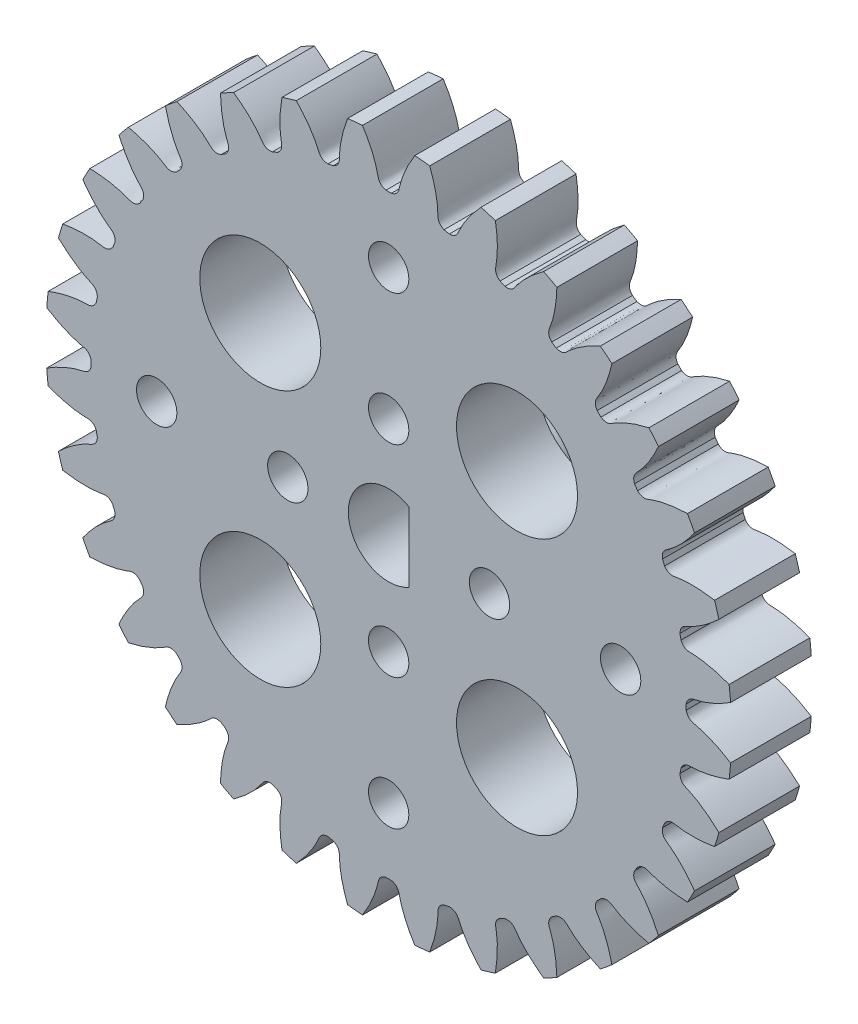
SolidWorks part; units mm, degrees
ref_plane "前视基准面" through (0, 0, 0) normal (0, 0, 1) x (1, 0, 0)
ref_plane "上视基准面" through (0, 0, 0) normal (0, 1, 0) x (1, 0, 0)
ref_plane "右视基准面" through (0, 0, 0) normal (1, 0, 0) x (0, 0, -1)
sketch "草图1" plane through (0, 0, 0) normal (0, 0, 1) x (1, 0, 0)
  arc A0 (-500.8621, -21.0203) -> (-500.9144, -20.7574) centre (-515.3543, -23.7663) ccw
  arc A1 (-500.9144, -26.7753) -> (-500.8621, -26.5123) centre (-515.3543, -23.7663) ccw
  arc A2 (-499.1979, -29.0552) -> (-498.9824, -28.3448) centre (-515.3543, -23.7663) ccw
  arc A3 (-501.7789, -29.5345) -> (-501.6763, -29.2869) centre (-515.3543, -23.7663) ccw
  arc A4 (-505.0196, -34.2905) -> (-504.8301, -34.101) centre (-515.3543, -23.7663) ccw
  arc A5 (-504.8591, -37.1399) -> (-504.2852, -36.6689) centre (-515.3543, -23.7663) ccw
  arc A6 (-507.2714, -36.1045) -> (-507.0485, -35.9555) centre (-515.3543, -23.7663) ccw
  arc A7 (-507.6698, -38.9304) -> (-507.0151, -38.5805) centre (-515.3543, -23.7663) ccw
  arc A8 (-509.8337, -37.4443) -> (-509.5861, -37.3417) centre (-515.3543, -23.7663) ccw
  arc A9 (-510.7758, -40.1382) -> (-510.0654, -39.9227) centre (-515.3543, -23.7663) ccw
  arc A10 (-512.6083, -38.2585) -> (-512.3453, -38.2062) centre (-515.3543, -23.7663) ccw
  arc A11 (-521.1224, -37.3417) -> (-520.8748, -37.4443) centre (-515.3543, -23.7663) ccw
  arc A12 (-523.6934, -38.5805) -> (-523.0388, -38.9304) centre (-515.3543, -23.7663) ccw
  arc A13 (-523.66, -35.9555) -> (-523.4371, -36.1045) centre (-515.3543, -23.7663) ccw
  arc A14 (-526.4233, -36.6689) -> (-525.8495, -37.1399) centre (-515.3543, -23.7663) ccw
  arc A15 (-525.8784, -34.101) -> (-525.6889, -34.2905) centre (-515.3543, -23.7663) ccw
  arc A16 (-528.7278, -34.2615) -> (-528.2568, -34.8354) centre (-515.3543, -23.7663) ccw
  arc A17 (-527.6924, -31.8492) -> (-527.5435, -32.0721) centre (-515.3543, -23.7663) ccw
  arc A18 (-530.5183, -31.4508) -> (-530.1684, -32.1055) centre (-515.3543, -23.7663) ccw
  arc A19 (-529.0322, -29.2869) -> (-528.9296, -29.5345) centre (-515.3543, -23.7663) ccw
  arc A20 (-531.7261, -28.3448) -> (-531.5106, -29.0552) centre (-515.3543, -23.7663) ccw
  arc A21 (-529.8464, -26.5123) -> (-529.7941, -26.7753) centre (-515.3543, -23.7663) ccw
  arc A22 (-529.7941, -20.7574) -> (-529.8464, -21.0203) centre (-515.3543, -23.7663) ccw
  arc A23 (-531.5106, -18.4775) -> (-531.7261, -19.1879) centre (-515.3543, -23.7663) ccw
  arc A24 (-528.9296, -17.9982) -> (-529.0322, -18.2458) centre (-515.3543, -23.7663) ccw
  arc A25 (-530.1684, -15.4272) -> (-530.5183, -16.0819) centre (-515.3543, -23.7663) ccw
  arc A26 (-527.5435, -15.4606) -> (-527.6924, -15.6835) centre (-515.3543, -23.7663) ccw
  arc A27 (-528.2568, -12.6973) -> (-528.7278, -13.2711) centre (-515.3543, -23.7663) ccw
  arc A28 (-525.6889, -13.2422) -> (-525.8784, -13.4317) centre (-515.3543, -23.7663) ccw
  arc A29 (-525.8495, -10.3928) -> (-526.4233, -10.8638) centre (-515.3543, -23.7663) ccw
  arc A30 (-523.4371, -11.4282) -> (-523.66, -11.5771) centre (-515.3543, -23.7663) ccw
  arc A31 (-523.0388, -8.6023) -> (-523.6934, -8.9522) centre (-515.3543, -23.7663) ccw
  arc A32 (-520.8748, -10.0884) -> (-521.1224, -10.191) centre (-515.3543, -23.7663) ccw
  arc A33 (-519.9327, -7.3945) -> (-520.6431, -7.61) centre (-515.3543, -23.7663) ccw
  arc A34 (-518.1003, -9.2742) -> (-518.3632, -9.3265) centre (-515.3543, -23.7663) ccw
  arc A35 (-515.2202, -9.017) -> (-515.4883, -9.017) centre (-515.3543, -23.7663) ccw
  arc A36 (-509.5861, -10.191) -> (-509.8337, -10.0884) centre (-515.3543, -23.7663) ccw
  arc A37 (-507.0485, -11.5771) -> (-507.2714, -11.4282) centre (-515.3543, -23.7663) ccw
  arc A38 (-504.8301, -13.4317) -> (-505.0196, -13.2422) centre (-515.3543, -23.7663) ccw
  arc A39 (-501.9808, -13.2711) -> (-502.4517, -12.6973) centre (-515.3543, -23.7663) ccw
  arc A40 (-503.0161, -15.6835) -> (-503.1651, -15.4606) centre (-515.3543, -23.7663) ccw
  arc A41 (-500.1902, -16.0819) -> (-500.5401, -15.4272) centre (-515.3543, -23.7663) ccw
  arc A42 (-501.6763, -18.2458) -> (-501.7789, -17.9982) centre (-515.3543, -23.7663) ccw
  arc A43 (-498.9824, -19.1879) -> (-499.1979, -18.4775) centre (-515.3543, -23.7663) ccw
  circle A44 centre (-515.3543, -23.7663) radius 2
  circle A45 centre (-510.3543, -23.7663) radius 1
  circle A46 centre (-515.3543, -18.7663) radius 1
  circle A47 centre (-520.3543, -23.7663) radius 1
  circle A48 centre (-515.3543, -28.7663) radius 1
  arc A49 (-498.4765, -25.8016) -> (-498.4038, -25.0629) centre (-515.3543, -23.7663) ccw
  arc A50 (-518.3632, -38.2062) -> (-518.1003, -38.2585) centre (-515.3543, -23.7663) ccw
  arc A51 (-512.3453, -9.3265) -> (-512.6083, -9.2742) centre (-515.3543, -23.7663) ccw
  arc A52 (-515.4883, -38.5157) -> (-515.2202, -38.5157) centre (-515.3543, -23.7663) ccw
  arc A53 (-514.0578, -40.7168) -> (-513.319, -40.6441) centre (-515.3543, -23.7663) ccw
  arc A54 (-517.3895, -40.6441) -> (-516.6508, -40.7168) centre (-515.3543, -23.7663) ccw
  arc A55 (-520.6431, -39.9227) -> (-519.9327, -40.1382) centre (-515.3543, -23.7663) ccw
  arc A56 (-502.4517, -34.8354) -> (-501.9808, -34.2615) centre (-515.3543, -23.7663) ccw
  arc A57 (-530.1037, -23.6323) -> (-530.1037, -23.9004) centre (-515.3543, -23.7663) ccw
  arc A58 (-532.3048, -25.0629) -> (-532.232, -25.8016) centre (-515.3543, -23.7663) ccw
  arc A59 (-532.232, -21.7311) -> (-532.3048, -22.4698) centre (-515.3543, -23.7663) ccw
  arc A60 (-500.5401, -32.1055) -> (-500.1902, -31.4508) centre (-515.3543, -23.7663) ccw
  arc A61 (-503.1651, -32.0721) -> (-503.0161, -31.8492) centre (-515.3543, -23.7663) ccw
  arc A62 (-516.6508, -6.8159) -> (-517.3895, -6.8886) centre (-515.3543, -23.7663) ccw
  arc A63 (-513.319, -6.8886) -> (-514.0578, -6.8159) centre (-515.3543, -23.7663) ccw
  arc A64 (-510.0654, -7.61) -> (-510.7758, -7.3945) centre (-515.3543, -23.7663) ccw
  arc A65 (-507.0151, -8.9522) -> (-507.6698, -8.6023) centre (-515.3543, -23.7663) ccw
  arc A66 (-504.2852, -10.8638) -> (-504.8591, -10.3928) centre (-515.3543, -23.7663) ccw
  arc A67 (-500.6049, -23.9004) -> (-500.6049, -23.6323) centre (-515.3543, -23.7663) ccw
  arc A68 (-498.4038, -22.4698) -> (-498.4765, -21.7311) centre (-515.3543, -23.7663) ccw
  circle A69 centre (-508.9903, -30.1303) radius 3
  circle A70 centre (-508.9903, -17.4024) radius 3
  circle A71 centre (-521.7182, -17.4024) radius 3
  circle A72 centre (-521.7182, -30.1303) radius 3
  circle A73 centre (-503.8543, -23.7663) radius 1
  circle A74 centre (-515.3543, -12.2663) radius 1
  circle A75 centre (-526.8543, -23.7663) radius 1
  circle A76 centre (-515.3543, -35.2663) radius 1
  spline S0 degree 3 poles (-500.8621, -21.0203) (-500.7088, -21.3516) (-500.4527, -21.3206) (-500.1768, -21.332) (-500.1101, -21.336) (-500.0094, -21.3441) (-499.8689, -21.3599) (-499.6833, -21.3881) (-499.4754, -21.4283) (-499.2458, -21.4823) (-498.9954, -21.5519) (-498.7361, -21.6351) (-498.5615, -21.6985) (-498.4765, -21.7311) knots 0 0 0 0 0.124533 0.135329 0.147193 0.160126 0.189198 0.222544 0.260164 0.302059 0.348227 0.39867 0.447185 0.447185 0.447185 0.447185
  spline S1 degree 3 poles (-500.8621, -26.5123) (-500.7088, -26.1811) (-500.4527, -26.2121) (-500.1768, -26.2007) (-500.1101, -26.1967) (-500.0094, -26.1885) (-499.8689, -26.1728) (-499.6833, -26.1445) (-499.4754, -26.1043) (-499.2458, -26.0504) (-498.9954, -25.9808) (-498.7361, -25.8975) (-498.5615, -25.8342) (-498.4765, -25.8016) knots 0 0 0 0 0.124533 0.135329 0.147193 0.160126 0.189198 0.222544 0.260164 0.302059 0.348227 0.39867 0.447185 0.447185 0.447185 0.447185
  spline S2 degree 3 poles (-500.9144, -26.7753) (-500.8995, -27.14) (-500.651, -27.2093) (-500.4005, -27.3255) (-500.3405, -27.3547) (-500.2505, -27.4008) (-500.1267, -27.469) (-499.9661, -27.5662) (-499.7894, -27.6829) (-499.5979, -27.8206) (-499.3932, -27.9807) (-499.1855, -28.1569) (-499.0485, -28.2822) (-498.9824, -28.3448) knots 0 0 0 0 0.124533 0.135329 0.147193 0.160126 0.189198 0.222544 0.260164 0.302059 0.348227 0.39867 0.447185 0.447185 0.447185 0.447185
  spline S3 degree 3 poles (-501.6763, -29.2869) (-501.4613, -28.9919) (-501.2162, -29.0723) (-500.9433, -29.1149) (-500.8772, -29.1239) (-500.7768, -29.1356) (-500.6359, -29.1476) (-500.4484, -29.1561) (-500.2366, -29.1572) (-500.0009, -29.1491) (-499.7417, -29.1297) (-499.4712, -29.0986) (-499.2876, -29.0705) (-499.1979, -29.0552) knots 0 0 0 0 0.124533 0.135329 0.147193 0.160126 0.189198 0.222544 0.260164 0.302059 0.348227 0.39867 0.447185 0.447185 0.447185 0.447185
  spline S4 degree 3 poles (-501.7789, -29.5345) (-501.8354, -29.8951) (-501.6052, -30.0116) (-501.3822, -30.1744) (-501.329, -30.2148) (-501.2498, -30.2775) (-501.1417, -30.3687) (-501.0031, -30.4953) (-500.8525, -30.6442) (-500.6916, -30.8167) (-500.522, -31.0136) (-500.3527, -31.2269) (-500.2428, -31.3766) (-500.1902, -31.4508) knots 0 0 0 0 0.124533 0.135329 0.147193 0.160126 0.189198 0.222544 0.260164 0.302059 0.348227 0.39867 0.447185 0.447185 0.447185 0.447185
  spline S5 degree 3 poles (-504.8301, -34.101) (-504.5186, -33.9107) (-504.3228, -34.0788) (-504.0871, -34.2226) (-504.0294, -34.2563) (-503.9412, -34.3055) (-503.8156, -34.3705) (-503.6456, -34.4501) (-503.4504, -34.5322) (-503.2295, -34.6148) (-502.9826, -34.6961) (-502.7208, -34.7709) (-502.5404, -34.8152) (-502.4517, -34.8354) knots 0 0 0 0 0.124533 0.135329 0.147193 0.160126 0.189198 0.222544 0.260164 0.302059 0.348227 0.39867 0.447185 0.447185 0.447185 0.447185
  spline S6 degree 3 poles (-505.0196, -34.2905) (-505.2099, -34.602) (-505.0418, -34.7978) (-504.898, -35.0335) (-504.8643, -35.0912) (-504.8151, -35.1794) (-504.7501, -35.305) (-504.6705, -35.475) (-504.5885, -35.6703) (-504.5058, -35.8911) (-504.4245, -36.138) (-504.3497, -36.3998) (-504.3054, -36.5802) (-504.2852, -36.6689) knots 0 0 0 0 0.124533 0.135329 0.147193 0.160126 0.189198 0.222544 0.260164 0.302059 0.348227 0.39867 0.447185 0.447185 0.447185 0.447185
  spline S7 degree 3 poles (-507.0485, -35.9555) (-506.7058, -35.8298) (-506.5467, -36.0328) (-506.3435, -36.2198) (-506.2935, -36.2641) (-506.2165, -36.3296) (-506.1061, -36.4178) (-505.9549, -36.529) (-505.7794, -36.6476) (-505.5789, -36.7718) (-505.3526, -36.8997) (-505.1104, -37.0242) (-504.9422, -37.1028) (-504.8591, -37.1399) knots 0 0 0 0 0.124533 0.135329 0.147193 0.160126 0.189198 0.222544 0.260164 0.302059 0.348227 0.39867 0.447185 0.447185 0.447185 0.447185
  spline S8 degree 3 poles (-507.2714, -36.1045) (-507.5187, -36.3729) (-507.3921, -36.5977) (-507.2971, -36.8569) (-507.2753, -36.9201) (-507.2442, -37.0162) (-507.205, -37.1521) (-507.1601, -37.3343) (-507.1177, -37.5418) (-507.0797, -37.7746) (-507.0481, -38.0326) (-507.0258, -38.304) (-507.0176, -38.4895) (-507.0151, -38.5805) knots 0 0 0 0 0.124533 0.135329 0.147193 0.160126 0.189198 0.222544 0.260164 0.302059 0.348227 0.39867 0.447185 0.447185 0.447185 0.447185
  spline S9 degree 3 poles (-509.5861, -37.3417) (-509.2255, -37.2852) (-509.109, -37.5154) (-508.9462, -37.7384) (-508.9058, -37.7916) (-508.8431, -37.8708) (-508.752, -37.979) (-508.6253, -38.1175) (-508.4764, -38.2681) (-508.304, -38.429) (-508.107, -38.5986) (-507.8937, -38.7679) (-507.7441, -38.8778) (-507.6698, -38.9304) knots 0 0 0 0 0.124533 0.135329 0.147193 0.160126 0.189198 0.222544 0.260164 0.302059 0.348227 0.39867 0.447185 0.447185 0.447185 0.447185
  spline S10 degree 3 poles (-509.8337, -37.4443) (-510.1287, -37.6593) (-510.0483, -37.9045) (-510.0057, -38.1773) (-509.9967, -38.2434) (-509.985, -38.3438) (-509.973, -38.4847) (-509.9645, -38.6722) (-509.9634, -38.884) (-509.9715, -39.1197) (-509.9909, -39.3789) (-510.022, -39.6494) (-510.0501, -39.833) (-510.0654, -39.9227) knots 0 0 0 0 0.124533 0.135329 0.147193 0.160126 0.189198 0.222544 0.260164 0.302059 0.348227 0.39867 0.447185 0.447185 0.447185 0.447185
  spline S11 degree 3 poles (-512.3453, -38.2062) (-511.9806, -38.2211) (-511.9113, -38.4696) (-511.7951, -38.7201) (-511.7659, -38.7801) (-511.7199, -38.8701) (-511.6516, -38.9939) (-511.5544, -39.1545) (-511.4377, -39.3312) (-511.3, -39.5227) (-511.1399, -39.7274) (-510.9637, -39.9351) (-510.8384, -40.0721) (-510.7758, -40.1382) knots 0 0 0 0 0.124533 0.135329 0.147193 0.160126 0.189198 0.222544 0.260164 0.302059 0.348227 0.39867 0.447185 0.447185 0.447185 0.447185
  spline S12 degree 3 poles (-512.6083, -38.2585) (-512.9395, -38.4118) (-512.9085, -38.6679) (-512.9199, -38.9438) (-512.924, -39.0105) (-512.9321, -39.1112) (-512.9478, -39.2517) (-512.9761, -39.4373) (-513.0163, -39.6452) (-513.0703, -39.8748) (-513.1398, -40.1253) (-513.2231, -40.3845) (-513.2865, -40.5591) (-513.319, -40.6441) knots 0 0 0 0 0.124533 0.135329 0.147193 0.160126 0.189198 0.222544 0.260164 0.302059 0.348227 0.39867 0.447185 0.447185 0.447185 0.447185
  spline S13 degree 3 poles (-520.8748, -37.4443) (-520.5798, -37.6593) (-520.6602, -37.9045) (-520.7028, -38.1773) (-520.7119, -38.2434) (-520.7236, -38.3438) (-520.7356, -38.4847) (-520.744, -38.6722) (-520.7452, -38.884) (-520.737, -39.1197) (-520.7177, -39.3789) (-520.6866, -39.6494) (-520.6584, -39.833) (-520.6431, -39.9227) knots 0 0 0 0 0.124533 0.135329 0.147193 0.160126 0.189198 0.222544 0.260164 0.302059 0.348227 0.39867 0.447185 0.447185 0.447185 0.447185
  spline S14 degree 3 poles (-521.1224, -37.3417) (-521.4831, -37.2852) (-521.5996, -37.5154) (-521.7624, -37.7384) (-521.8027, -37.7916) (-521.8654, -37.8708) (-521.9566, -37.979) (-522.0832, -38.1175) (-522.2321, -38.2681) (-522.4046, -38.429) (-522.6015, -38.5986) (-522.8148, -38.7679) (-522.9645, -38.8778) (-523.0388, -38.9304) knots 0 0 0 0 0.124533 0.135329 0.147193 0.160126 0.189198 0.222544 0.260164 0.302059 0.348227 0.39867 0.447185 0.447185 0.447185 0.447185
  spline S15 degree 3 poles (-523.4371, -36.1045) (-523.1898, -36.3729) (-523.3165, -36.5977) (-523.4115, -36.8569) (-523.4333, -36.9201) (-523.4643, -37.0162) (-523.5036, -37.1521) (-523.5485, -37.3343) (-523.5909, -37.5418) (-523.6289, -37.7746) (-523.6605, -38.0326) (-523.6827, -38.304) (-523.691, -38.4895) (-523.6934, -38.5805) knots 0 0 0 0 0.124533 0.135329 0.147193 0.160126 0.189198 0.222544 0.260164 0.302059 0.348227 0.39867 0.447185 0.447185 0.447185 0.447185
  spline S16 degree 3 poles (-523.66, -35.9555) (-524.0027, -35.8298) (-524.1619, -36.0328) (-524.365, -36.2198) (-524.415, -36.2641) (-524.492, -36.3296) (-524.6025, -36.4178) (-524.7537, -36.529) (-524.9291, -36.6476) (-525.1296, -36.7718) (-525.3559, -36.8997) (-525.5981, -37.0242) (-525.7663, -37.1028) (-525.8495, -37.1399) knots 0 0 0 0 0.124533 0.135329 0.147193 0.160126 0.189198 0.222544 0.260164 0.302059 0.348227 0.39867 0.447185 0.447185 0.447185 0.447185
  spline S17 degree 3 poles (-525.6889, -34.2905) (-525.4987, -34.602) (-525.6667, -34.7978) (-525.8105, -35.0335) (-525.8442, -35.0912) (-525.8934, -35.1794) (-525.9584, -35.305) (-526.038, -35.475) (-526.1201, -35.6703) (-526.2027, -35.8911) (-526.2841, -36.138) (-526.3589, -36.3998) (-526.4031, -36.5802) (-526.4233, -36.6689) knots 0 0 0 0 0.124533 0.135329 0.147193 0.160126 0.189198 0.222544 0.260164 0.302059 0.348227 0.39867 0.447185 0.447185 0.447185 0.447185
  spline S18 degree 3 poles (-525.8784, -34.101) (-526.19, -33.9107) (-526.3857, -34.0788) (-526.6214, -34.2226) (-526.6791, -34.2563) (-526.7674, -34.3055) (-526.8929, -34.3705) (-527.0629, -34.4501) (-527.2582, -34.5322) (-527.4791, -34.6148) (-527.7259, -34.6961) (-527.9878, -34.7709) (-528.1681, -34.8152) (-528.2568, -34.8354) knots 0 0 0 0 0.124533 0.135329 0.147193 0.160126 0.189198 0.222544 0.260164 0.302059 0.348227 0.39867 0.447185 0.447185 0.447185 0.447185
  spline S19 degree 3 poles (-527.5435, -32.0721) (-527.4177, -32.4148) (-527.6207, -32.5739) (-527.8077, -32.7771) (-527.852, -32.8271) (-527.9175, -32.9041) (-528.0057, -33.0145) (-528.117, -33.1658) (-528.2356, -33.3412) (-528.3597, -33.5417) (-528.4876, -33.768) (-528.6121, -34.0102) (-528.6907, -34.1784) (-528.7278, -34.2615) knots 0 0 0 0 0.124533 0.135329 0.147193 0.160126 0.189198 0.222544 0.260164 0.302059 0.348227 0.39867 0.447185 0.447185 0.447185 0.447185
  spline S20 degree 3 poles (-527.6924, -31.8492) (-527.9608, -31.6019) (-528.1856, -31.7285) (-528.4449, -31.8235) (-528.508, -31.8453) (-528.6042, -31.8764) (-528.74, -31.9157) (-528.9223, -31.9605) (-529.1298, -32.003) (-529.3625, -32.0409) (-529.6205, -32.0725) (-529.8919, -32.0948) (-530.0774, -32.103) (-530.1684, -32.1055) knots 0 0 0 0 0.124533 0.135329 0.147193 0.160126 0.189198 0.222544 0.260164 0.302059 0.348227 0.39867 0.447185 0.447185 0.447185 0.447185
  spline S21 degree 3 poles (-528.9296, -29.5345) (-528.8731, -29.8951) (-529.1033, -30.0116) (-529.3263, -30.1744) (-529.3795, -30.2148) (-529.4588, -30.2775) (-529.5669, -30.3687) (-529.7055, -30.4953) (-529.856, -30.6442) (-530.0169, -30.8167) (-530.1865, -31.0136) (-530.3558, -31.2269) (-530.4657, -31.3766) (-530.5183, -31.4508) knots 0 0 0 0 0.124533 0.135329 0.147193 0.160126 0.189198 0.222544 0.260164 0.302059 0.348227 0.39867 0.447185 0.447185 0.447185 0.447185
  spline S22 degree 3 poles (-529.0322, -29.2869) (-529.2472, -28.9919) (-529.4924, -29.0723) (-529.7652, -29.1149) (-529.8314, -29.1239) (-529.9318, -29.1356) (-530.0726, -29.1476) (-530.2602, -29.1561) (-530.4719, -29.1572) (-530.7076, -29.1491) (-530.9668, -29.1297) (-531.2374, -29.0986) (-531.4209, -29.0705) (-531.5106, -29.0552) knots 0 0 0 0 0.124533 0.135329 0.147193 0.160126 0.189198 0.222544 0.260164 0.302059 0.348227 0.39867 0.447185 0.447185 0.447185 0.447185
  spline S23 degree 3 poles (-529.7941, -26.7753) (-529.809, -27.14) (-530.0575, -27.2093) (-530.308, -27.3255) (-530.3681, -27.3547) (-530.458, -27.4008) (-530.5818, -27.469) (-530.7425, -27.5662) (-530.9192, -27.6829) (-531.1106, -27.8206) (-531.3154, -27.9807) (-531.523, -28.1569) (-531.66, -28.2822) (-531.7261, -28.3448) knots 0 0 0 0 0.124533 0.135329 0.147193 0.160126 0.189198 0.222544 0.260164 0.302059 0.348227 0.39867 0.447185 0.447185 0.447185 0.447185
  spline S24 degree 3 poles (-529.8464, -26.5123) (-529.9997, -26.1811) (-530.2559, -26.2121) (-530.5317, -26.2007) (-530.5984, -26.1967) (-530.6992, -26.1885) (-530.8397, -26.1728) (-531.0252, -26.1445) (-531.2332, -26.1043) (-531.4628, -26.0504) (-531.7132, -25.9808) (-531.9725, -25.8975) (-532.147, -25.8342) (-532.232, -25.8016) knots 0 0 0 0 0.124533 0.135329 0.147193 0.160126 0.189198 0.222544 0.260164 0.302059 0.348227 0.39867 0.447185 0.447185 0.447185 0.447185
  spline S25 degree 3 poles (-530.1037, -23.6323) (-530.1894, -23.2775) (-530.4467, -23.258) (-530.715, -23.1929) (-530.7796, -23.176) (-530.8769, -23.1484) (-531.0116, -23.1055) (-531.1881, -23.0416) (-531.3842, -22.9616) (-531.5988, -22.8639) (-531.8309, -22.7468) (-532.0689, -22.6145) (-532.2277, -22.5183) (-532.3048, -22.4698) knots 0 0 0 0 0.124533 0.135329 0.147193 0.160126 0.189198 0.222544 0.260164 0.302059 0.348227 0.39867 0.447185 0.447185 0.447185 0.447185
  spline S26 degree 3 poles (-529.8464, -21.0203) (-529.9997, -21.3516) (-530.2559, -21.3206) (-530.5317, -21.332) (-530.5984, -21.336) (-530.6992, -21.3441) (-530.8397, -21.3599) (-531.0252, -21.3881) (-531.2332, -21.4283) (-531.4628, -21.4823) (-531.7132, -21.5519) (-531.9725, -21.6351) (-532.147, -21.6985) (-532.232, -21.7311) knots 0 0 0 0 0.124533 0.135329 0.147193 0.160126 0.189198 0.222544 0.260164 0.302059 0.348227 0.39867 0.447185 0.447185 0.447185 0.447185
  spline S27 degree 3 poles (-529.7941, -20.7574) (-529.809, -20.3927) (-530.0575, -20.3234) (-530.308, -20.2072) (-530.3681, -20.178) (-530.458, -20.1319) (-530.5818, -20.0636) (-530.7425, -19.9665) (-530.9192, -19.8498) (-531.1106, -19.712) (-531.3154, -19.552) (-531.523, -19.3758) (-531.66, -19.2505) (-531.7261, -19.1879) knots 0 0 0 0 0.124533 0.135329 0.147193 0.160126 0.189198 0.222544 0.260164 0.302059 0.348227 0.39867 0.447185 0.447185 0.447185 0.447185
  spline S28 degree 3 poles (-529.0322, -18.2458) (-529.2472, -18.5408) (-529.4924, -18.4604) (-529.7652, -18.4178) (-529.8314, -18.4087) (-529.9318, -18.397) (-530.0726, -18.385) (-530.2602, -18.3766) (-530.4719, -18.3755) (-530.7076, -18.3836) (-530.9668, -18.403) (-531.2374, -18.434) (-531.4209, -18.4622) (-531.5106, -18.4775) knots 0 0 0 0 0.124533 0.135329 0.147193 0.160126 0.189198 0.222544 0.260164 0.302059 0.348227 0.39867 0.447185 0.447185 0.447185 0.447185
  spline S29 degree 3 poles (-528.9296, -17.9982) (-528.8731, -17.6376) (-529.1033, -17.5211) (-529.3263, -17.3583) (-529.3795, -17.3179) (-529.4588, -17.2552) (-529.5669, -17.164) (-529.7055, -17.0374) (-529.856, -16.8885) (-530.0169, -16.716) (-530.1865, -16.5191) (-530.3558, -16.3058) (-530.4657, -16.1561) (-530.5183, -16.0819) knots 0 0 0 0 0.124533 0.135329 0.147193 0.160126 0.189198 0.222544 0.260164 0.302059 0.348227 0.39867 0.447185 0.447185 0.447185 0.447185
  spline S30 degree 3 poles (-527.6924, -15.6835) (-527.9608, -15.9308) (-528.1856, -15.8041) (-528.4449, -15.7091) (-528.508, -15.6873) (-528.6042, -15.6563) (-528.74, -15.617) (-528.9223, -15.5721) (-529.1298, -15.5297) (-529.3625, -15.4917) (-529.6205, -15.4602) (-529.8919, -15.4379) (-530.0774, -15.4296) (-530.1684, -15.4272) knots 0 0 0 0 0.124533 0.135329 0.147193 0.160126 0.189198 0.222544 0.260164 0.302059 0.348227 0.39867 0.447185 0.447185 0.447185 0.447185
  spline S31 degree 3 poles (-527.5435, -15.4606) (-527.4177, -15.1179) (-527.6207, -14.9588) (-527.8077, -14.7556) (-527.852, -14.7056) (-527.9175, -14.6286) (-528.0057, -14.5181) (-528.117, -14.3669) (-528.2356, -14.1915) (-528.3597, -13.991) (-528.4876, -13.7647) (-528.6121, -13.5225) (-528.6907, -13.3543) (-528.7278, -13.2711) knots 0 0 0 0 0.124533 0.135329 0.147193 0.160126 0.189198 0.222544 0.260164 0.302059 0.348227 0.39867 0.447185 0.447185 0.447185 0.447185
  spline S32 degree 3 poles (-525.8784, -13.4317) (-526.19, -13.6219) (-526.3857, -13.4539) (-526.6214, -13.3101) (-526.6791, -13.2764) (-526.7674, -13.2272) (-526.8929, -13.1622) (-527.0629, -13.0826) (-527.2582, -13.0005) (-527.4791, -12.9179) (-527.7259, -12.8366) (-527.9878, -12.7617) (-528.1681, -12.7175) (-528.2568, -12.6973) knots 0 0 0 0 0.124533 0.135329 0.147193 0.160126 0.189198 0.222544 0.260164 0.302059 0.348227 0.39867 0.447185 0.447185 0.447185 0.447185
  spline S33 degree 3 poles (-525.6889, -13.2422) (-525.4987, -12.9306) (-525.6667, -12.7349) (-525.8105, -12.4992) (-525.8442, -12.4415) (-525.8934, -12.3532) (-525.9584, -12.2277) (-526.038, -12.0577) (-526.1201, -11.8624) (-526.2027, -11.6416) (-526.2841, -11.3947) (-526.3589, -11.1329) (-526.4031, -10.9525) (-526.4233, -10.8638) knots 0 0 0 0 0.124533 0.135329 0.147193 0.160126 0.189198 0.222544 0.260164 0.302059 0.348227 0.39867 0.447185 0.447185 0.447185 0.447185
  spline S34 degree 3 poles (-523.66, -11.5771) (-524.0027, -11.7029) (-524.1619, -11.4999) (-524.365, -11.3129) (-524.415, -11.2686) (-524.492, -11.2031) (-524.6025, -11.1149) (-524.7537, -11.0036) (-524.9291, -10.885) (-525.1296, -10.7609) (-525.3559, -10.633) (-525.5981, -10.5085) (-525.7663, -10.4299) (-525.8495, -10.3928) knots 0 0 0 0 0.124533 0.135329 0.147193 0.160126 0.189198 0.222544 0.260164 0.302059 0.348227 0.39867 0.447185 0.447185 0.447185 0.447185
  spline S35 degree 3 poles (-523.4371, -11.4282) (-523.1898, -11.1598) (-523.3165, -10.935) (-523.4115, -10.6758) (-523.4333, -10.6126) (-523.4643, -10.5165) (-523.5036, -10.3806) (-523.5485, -10.1983) (-523.5909, -9.9909) (-523.6289, -9.7581) (-523.6605, -9.5001) (-523.6827, -9.2287) (-523.691, -9.0432) (-523.6934, -8.9522) knots 0 0 0 0 0.124533 0.135329 0.147193 0.160126 0.189198 0.222544 0.260164 0.302059 0.348227 0.39867 0.447185 0.447185 0.447185 0.447185
  spline S36 degree 3 poles (-521.1224, -10.191) (-521.4831, -10.2475) (-521.5996, -10.0173) (-521.7624, -9.7943) (-521.8027, -9.7411) (-521.8654, -9.6618) (-521.9566, -9.5537) (-522.0832, -9.4151) (-522.2321, -9.2646) (-522.4046, -9.1037) (-522.6015, -8.9341) (-522.8148, -8.7648) (-522.9645, -8.6549) (-523.0388, -8.6023) knots 0 0 0 0 0.124533 0.135329 0.147193 0.160126 0.189198 0.222544 0.260164 0.302059 0.348227 0.39867 0.447185 0.447185 0.447185 0.447185
  spline S37 degree 3 poles (-520.8748, -10.0884) (-520.5798, -9.8734) (-520.6602, -9.6282) (-520.7028, -9.3554) (-520.7119, -9.2892) (-520.7236, -9.1889) (-520.7356, -9.048) (-520.744, -8.8604) (-520.7452, -8.6487) (-520.737, -8.413) (-520.7177, -8.1538) (-520.6866, -7.8832) (-520.6584, -7.6997) (-520.6431, -7.61) knots 0 0 0 0 0.124533 0.135329 0.147193 0.160126 0.189198 0.222544 0.260164 0.302059 0.348227 0.39867 0.447185 0.447185 0.447185 0.447185
  spline S38 degree 3 poles (-518.3632, -9.3265) (-518.7279, -9.3116) (-518.7973, -9.0631) (-518.9134, -8.8126) (-518.9426, -8.7525) (-518.9887, -8.6626) (-519.057, -8.5388) (-519.1541, -8.3781) (-519.2708, -8.2014) (-519.4086, -8.01) (-519.5686, -7.8052) (-519.7448, -7.5976) (-519.8702, -7.4606) (-519.9327, -7.3945) knots 0 0 0 0 0.124533 0.135329 0.147193 0.160126 0.189198 0.222544 0.260164 0.302059 0.348227 0.39867 0.447185 0.447185 0.447185 0.447185
  spline S39 degree 3 poles (-518.1003, -9.2742) (-517.769, -9.1209) (-517.8, -8.8647) (-517.7886, -8.5889) (-517.7846, -8.5222) (-517.7765, -8.4215) (-517.7608, -8.2809) (-517.7325, -8.0954) (-517.6923, -7.8874) (-517.6383, -7.6579) (-517.5687, -7.4074) (-517.4855, -7.1482) (-517.4221, -6.9736) (-517.3895, -6.8886) knots 0 0 0 0 0.124533 0.135329 0.147193 0.160126 0.189198 0.222544 0.260164 0.302059 0.348227 0.39867 0.447185 0.447185 0.447185 0.447185
  spline S40 degree 3 poles (-515.4883, -9.017) (-515.8431, -8.9312) (-515.8626, -8.6739) (-515.9277, -8.4056) (-515.9446, -8.341) (-515.9723, -8.2438) (-516.0151, -8.109) (-516.079, -7.9325) (-516.159, -7.7364) (-516.2568, -7.5218) (-516.3738, -7.2897) (-516.5061, -7.0517) (-516.6023, -6.8929) (-516.6508, -6.8159) knots 0 0 0 0 0.124533 0.135329 0.147193 0.160126 0.189198 0.222544 0.260164 0.302059 0.348227 0.39867 0.447185 0.447185 0.447185 0.447185
  spline S41 degree 3 poles (-515.2202, -9.017) (-514.8654, -8.9312) (-514.8459, -8.6739) (-514.7808, -8.4056) (-514.7639, -8.341) (-514.7363, -8.2438) (-514.6935, -8.109) (-514.6295, -7.9325) (-514.5495, -7.7364) (-514.4518, -7.5218) (-514.3347, -7.2897) (-514.2025, -7.0517) (-514.1063, -6.8929) (-514.0578, -6.8159) knots 0 0 0 0 0.124533 0.135329 0.147193 0.160126 0.189198 0.222544 0.260164 0.302059 0.348227 0.39867 0.447185 0.447185 0.447185 0.447185
  spline S42 degree 3 poles (-509.8337, -10.0884) (-510.1287, -9.8734) (-510.0483, -9.6282) (-510.0057, -9.3554) (-509.9967, -9.2892) (-509.985, -9.1889) (-509.973, -9.048) (-509.9645, -8.8604) (-509.9634, -8.6487) (-509.9715, -8.413) (-509.9909, -8.1538) (-510.022, -7.8832) (-510.0501, -7.6997) (-510.0654, -7.61) knots 0 0 0 0 0.124533 0.135329 0.147193 0.160126 0.189198 0.222544 0.260164 0.302059 0.348227 0.39867 0.447185 0.447185 0.447185 0.447185
  spline S43 degree 3 poles (-509.5861, -10.191) (-509.2255, -10.2475) (-509.109, -10.0173) (-508.9462, -9.7943) (-508.9058, -9.7411) (-508.8431, -9.6618) (-508.752, -9.5537) (-508.6253, -9.4151) (-508.4764, -9.2646) (-508.304, -9.1037) (-508.107, -8.9341) (-507.8937, -8.7648) (-507.7441, -8.6549) (-507.6698, -8.6023) knots 0 0 0 0 0.124533 0.135329 0.147193 0.160126 0.189198 0.222544 0.260164 0.302059 0.348227 0.39867 0.447185 0.447185 0.447185 0.447185
  spline S44 degree 3 poles (-507.0485, -11.5771) (-506.7058, -11.7029) (-506.5467, -11.4999) (-506.3435, -11.3129) (-506.2935, -11.2686) (-506.2165, -11.2031) (-506.1061, -11.1149) (-505.9549, -11.0036) (-505.7794, -10.885) (-505.5789, -10.7609) (-505.3526, -10.633) (-505.1104, -10.5085) (-504.9422, -10.4299) (-504.8591, -10.3928) knots 0 0 0 0 0.124533 0.135329 0.147193 0.160126 0.189198 0.222544 0.260164 0.302059 0.348227 0.39867 0.447185 0.447185 0.447185 0.447185
  spline S45 degree 3 poles (-505.0196, -13.2422) (-505.2099, -12.9306) (-505.0418, -12.7349) (-504.898, -12.4992) (-504.8643, -12.4415) (-504.8151, -12.3532) (-504.7501, -12.2277) (-504.6705, -12.0577) (-504.5885, -11.8624) (-504.5058, -11.6416) (-504.4245, -11.3947) (-504.3497, -11.1329) (-504.3054, -10.9525) (-504.2852, -10.8638) knots 0 0 0 0 0.124533 0.135329 0.147193 0.160126 0.189198 0.222544 0.260164 0.302059 0.348227 0.39867 0.447185 0.447185 0.447185 0.447185
  spline S46 degree 3 poles (-504.8301, -13.4317) (-504.5186, -13.6219) (-504.3228, -13.4539) (-504.0871, -13.3101) (-504.0294, -13.2764) (-503.9412, -13.2272) (-503.8156, -13.1622) (-503.6456, -13.0826) (-503.4504, -13.0005) (-503.2295, -12.9179) (-502.9826, -12.8366) (-502.7208, -12.7617) (-502.5404, -12.7175) (-502.4517, -12.6973) knots 0 0 0 0 0.124533 0.135329 0.147193 0.160126 0.189198 0.222544 0.260164 0.302059 0.348227 0.39867 0.447185 0.447185 0.447185 0.447185
  spline S47 degree 3 poles (-503.1651, -15.4606) (-503.2908, -15.1179) (-503.0878, -14.9588) (-502.9008, -14.7556) (-502.8565, -14.7056) (-502.791, -14.6286) (-502.7028, -14.5181) (-502.5916, -14.3669) (-502.473, -14.1915) (-502.3488, -13.991) (-502.2209, -13.7647) (-502.0964, -13.5225) (-502.0179, -13.3543) (-501.9808, -13.2711) knots 0 0 0 0 0.124533 0.135329 0.147193 0.160126 0.189198 0.222544 0.260164 0.302059 0.348227 0.39867 0.447185 0.447185 0.447185 0.447185
  spline S48 degree 3 poles (-503.0161, -15.6835) (-502.7477, -15.9308) (-502.5229, -15.8041) (-502.2637, -15.7091) (-502.2006, -15.6873) (-502.1044, -15.6563) (-501.9685, -15.617) (-501.7863, -15.5721) (-501.5788, -15.5297) (-501.346, -15.4917) (-501.088, -15.4602) (-500.8166, -15.4379) (-500.6311, -15.4296) (-500.5401, -15.4272) knots 0 0 0 0 0.124533 0.135329 0.147193 0.160126 0.189198 0.222544 0.260164 0.302059 0.348227 0.39867 0.447185 0.447185 0.447185 0.447185
  spline S49 degree 3 poles (-501.7789, -17.9982) (-501.8354, -17.6376) (-501.6052, -17.5211) (-501.3822, -17.3583) (-501.329, -17.3179) (-501.2498, -17.2552) (-501.1417, -17.164) (-501.0031, -17.0374) (-500.8525, -16.8885) (-500.6916, -16.716) (-500.522, -16.5191) (-500.3527, -16.3058) (-500.2428, -16.1561) (-500.1902, -16.0819) knots 0 0 0 0 0.124533 0.135329 0.147193 0.160126 0.189198 0.222544 0.260164 0.302059 0.348227 0.39867 0.447185 0.447185 0.447185 0.447185
  spline S50 degree 3 poles (-501.6763, -18.2458) (-501.4613, -18.5408) (-501.2162, -18.4604) (-500.9433, -18.4178) (-500.8772, -18.4087) (-500.7768, -18.397) (-500.6359, -18.385) (-500.4484, -18.3766) (-500.2366, -18.3755) (-500.0009, -18.3836) (-499.7417, -18.403) (-499.4712, -18.434) (-499.2876, -18.4622) (-499.1979, -18.4775) knots 0 0 0 0 0.124533 0.135329 0.147193 0.160126 0.189198 0.222544 0.260164 0.302059 0.348227 0.39867 0.447185 0.447185 0.447185 0.447185
  spline S51 degree 3 poles (-500.9144, -20.7574) (-500.8995, -20.3927) (-500.651, -20.3234) (-500.4005, -20.2072) (-500.3405, -20.178) (-500.2505, -20.1319) (-500.1267, -20.0636) (-499.9661, -19.9665) (-499.7894, -19.8498) (-499.5979, -19.712) (-499.3932, -19.552) (-499.1855, -19.3758) (-499.0485, -19.2505) (-498.9824, -19.1879) knots 0 0 0 0 0.124533 0.135329 0.147193 0.160126 0.189198 0.222544 0.260164 0.302059 0.348227 0.39867 0.447185 0.447185 0.447185 0.447185
  spline S52 degree 3 poles (-518.3632, -38.2062) (-518.7279, -38.2211) (-518.7973, -38.4696) (-518.9134, -38.7201) (-518.9426, -38.7801) (-518.9887, -38.8701) (-519.057, -38.9939) (-519.1541, -39.1545) (-519.2708, -39.3312) (-519.4086, -39.5227) (-519.5686, -39.7274) (-519.7448, -39.9351) (-519.8702, -40.0721) (-519.9327, -40.1382) knots 0 0 0 0 0.124533 0.135329 0.147193 0.160126 0.189198 0.222544 0.260164 0.302059 0.348227 0.39867 0.447185 0.447185 0.447185 0.447185
  spline S53 degree 3 poles (-515.2202, -38.5157) (-514.8654, -38.6015) (-514.8459, -38.8588) (-514.7808, -39.1271) (-514.7639, -39.1917) (-514.7363, -39.2889) (-514.6935, -39.4237) (-514.6295, -39.6002) (-514.5495, -39.7963) (-514.4518, -40.0109) (-514.3347, -40.2429) (-514.2025, -40.481) (-514.1063, -40.6398) (-514.0578, -40.7168) knots 0 0 0 0 0.124533 0.135329 0.147193 0.160126 0.189198 0.222544 0.260164 0.302059 0.348227 0.39867 0.447185 0.447185 0.447185 0.447185
  spline S54 degree 3 poles (-515.4883, -38.5157) (-515.8431, -38.6015) (-515.8626, -38.8588) (-515.9277, -39.1271) (-515.9446, -39.1917) (-515.9723, -39.2889) (-516.0151, -39.4237) (-516.079, -39.6002) (-516.159, -39.7963) (-516.2568, -40.0109) (-516.3738, -40.2429) (-516.5061, -40.481) (-516.6023, -40.6398) (-516.6508, -40.7168) knots 0 0 0 0 0.124533 0.135329 0.147193 0.160126 0.189198 0.222544 0.260164 0.302059 0.348227 0.39867 0.447185 0.447185 0.447185 0.447185
  spline S55 degree 3 poles (-512.6083, -9.2742) (-512.9395, -9.1209) (-512.9085, -8.8647) (-512.9199, -8.5889) (-512.924, -8.5222) (-512.9321, -8.4215) (-512.9478, -8.2809) (-512.9761, -8.0954) (-513.0163, -7.8874) (-513.0703, -7.6579) (-513.1398, -7.4074) (-513.2231, -7.1482) (-513.2865, -6.9736) (-513.319, -6.8886) knots 0 0 0 0 0.124533 0.135329 0.147193 0.160126 0.189198 0.222544 0.260164 0.302059 0.348227 0.39867 0.447185 0.447185 0.447185 0.447185
  spline S56 degree 3 poles (-507.2714, -11.4282) (-507.5187, -11.1598) (-507.3921, -10.935) (-507.2971, -10.6758) (-507.2753, -10.6126) (-507.2442, -10.5165) (-507.205, -10.3806) (-507.1601, -10.1983) (-507.1177, -9.9909) (-507.0797, -9.7581) (-507.0481, -9.5001) (-507.0258, -9.2287) (-507.0176, -9.0432) (-507.0151, -8.9522) knots 0 0 0 0 0.124533 0.135329 0.147193 0.160126 0.189198 0.222544 0.260164 0.302059 0.348227 0.39867 0.447185 0.447185 0.447185 0.447185
  spline S57 degree 3 poles (-530.1037, -23.9004) (-530.1894, -24.2552) (-530.4467, -24.2747) (-530.715, -24.3398) (-530.7796, -24.3567) (-530.8769, -24.3843) (-531.0116, -24.4271) (-531.1881, -24.4911) (-531.3842, -24.5711) (-531.5988, -24.6688) (-531.8309, -24.7859) (-532.0689, -24.9181) (-532.2277, -25.0144) (-532.3048, -25.0629) knots 0 0 0 0 0.124533 0.135329 0.147193 0.160126 0.189198 0.222544 0.260164 0.302059 0.348227 0.39867 0.447185 0.447185 0.447185 0.447185
  spline S58 degree 3 poles (-518.1003, -38.2585) (-517.769, -38.4118) (-517.8, -38.6679) (-517.7886, -38.9438) (-517.7846, -39.0105) (-517.7765, -39.1112) (-517.7608, -39.2517) (-517.7325, -39.4373) (-517.6923, -39.6452) (-517.6383, -39.8748) (-517.5687, -40.1253) (-517.4855, -40.3845) (-517.4221, -40.5591) (-517.3895, -40.6441) knots 0 0 0 0 0.124533 0.135329 0.147193 0.160126 0.189198 0.222544 0.260164 0.302059 0.348227 0.39867 0.447185 0.447185 0.447185 0.447185
  spline S59 degree 3 poles (-503.0161, -31.8492) (-502.7477, -31.6019) (-502.5229, -31.7285) (-502.2637, -31.8235) (-502.2006, -31.8453) (-502.1044, -31.8764) (-501.9685, -31.9157) (-501.7863, -31.9605) (-501.5788, -32.003) (-501.346, -32.0409) (-501.088, -32.0725) (-500.8166, -32.0948) (-500.6311, -32.103) (-500.5401, -32.1055) knots 0 0 0 0 0.124533 0.135329 0.147193 0.160126 0.189198 0.222544 0.260164 0.302059 0.348227 0.39867 0.447185 0.447185 0.447185 0.447185
  spline S60 degree 3 poles (-503.1651, -32.0721) (-503.2908, -32.4148) (-503.0878, -32.5739) (-502.9008, -32.7771) (-502.8565, -32.8271) (-502.791, -32.9041) (-502.7028, -33.0145) (-502.5916, -33.1658) (-502.473, -33.3412) (-502.3488, -33.5417) (-502.2209, -33.768) (-502.0964, -34.0102) (-502.0179, -34.1784) (-501.9808, -34.2615) knots 0 0 0 0 0.124533 0.135329 0.147193 0.160126 0.189198 0.222544 0.260164 0.302059 0.348227 0.39867 0.447185 0.447185 0.447185 0.447185
  spline S61 degree 3 poles (-512.3453, -9.3265) (-511.9806, -9.3116) (-511.9113, -9.0631) (-511.7951, -8.8126) (-511.7659, -8.7525) (-511.7199, -8.6626) (-511.6516, -8.5388) (-511.5544, -8.3781) (-511.4377, -8.2014) (-511.3, -8.01) (-511.1399, -7.8052) (-510.9637, -7.5976) (-510.8384, -7.4606) (-510.7758, -7.3945) knots 0 0 0 0 0.124533 0.135329 0.147193 0.160126 0.189198 0.222544 0.260164 0.302059 0.348227 0.39867 0.447185 0.447185 0.447185 0.447185
  spline S62 degree 3 poles (-500.6049, -23.9004) (-500.5191, -24.2552) (-500.2619, -24.2747) (-499.9935, -24.3398) (-499.9289, -24.3567) (-499.8317, -24.3843) (-499.6969, -24.4271) (-499.5204, -24.4911) (-499.3244, -24.5711) (-499.1097, -24.6688) (-498.8777, -24.7859) (-498.6396, -24.9181) (-498.4808, -25.0144) (-498.4038, -25.0629) knots 0 0 0 0 0.124533 0.135329 0.147193 0.160126 0.189198 0.222544 0.260164 0.302059 0.348227 0.39867 0.447185 0.447185 0.447185 0.447185
  spline S63 degree 3 poles (-500.6049, -23.6323) (-500.5191, -23.2775) (-500.2619, -23.258) (-499.9935, -23.1929) (-499.9289, -23.176) (-499.8317, -23.1484) (-499.6969, -23.1055) (-499.5204, -23.0416) (-499.3244, -22.9616) (-499.1097, -22.8639) (-498.8777, -22.7468) (-498.6396, -22.6145) (-498.4808, -22.5183) (-498.4038, -22.4698) knots 0 0 0 0 0.124533 0.135329 0.147193 0.160126 0.189198 0.222544 0.260164 0.302059 0.348227 0.39867 0.447185 0.447185 0.447185 0.447185
extrude "凸台-拉伸1" add sketch "草图1" along normal blind 4
sketch "草图2" plane through (0, 0, 4) normal (0, 0, 1) x (1, 0, 0)
  line L0 (-514.3543, -22.0343) -> (-514.3543, -25.4984)
  arc A0 (-514.3543, -22.0343) -> (-514.3543, -25.4984) centre (-515.3543, -23.7663) ccw
  circle A1 centre (-515.3543, -23.7663) radius 3.25
  dimension "D2" = 4
  dimension "D3" = 6.5
  dimension "D1" = 1
extrude "凸台-拉伸2" add sketch "草图2" against normal blind 8
